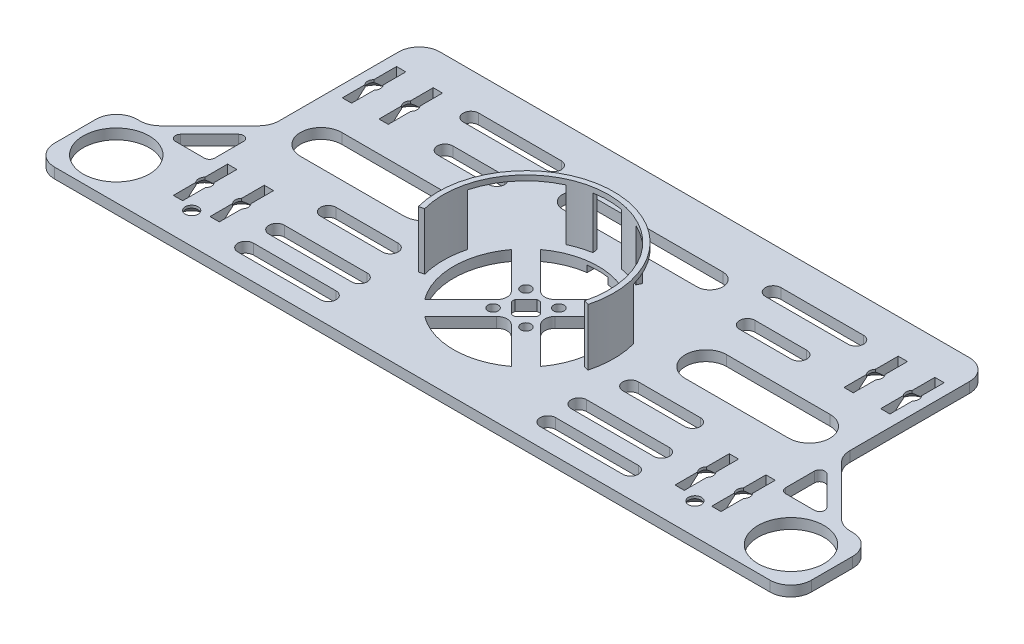
SolidWorks part; units mm, degrees
ref_plane "前视基准面" through (0, 0, 0) normal (0, 0, 1) x (1, 0, 0)
ref_plane "上视基准面" through (0, 0, 0) normal (0, 1, 0) x (1, 0, 0)
ref_plane "右视基准面" through (0, 0, 0) normal (1, 0, 0) x (0, 0, -1)
sketch "草图1" plane through (0, 0, 0) normal (0, 1, 0) x (1, 0, 0)
  line L0 (0, 0) -> (0, 46.1677) construction
  line L1 (-73.25, 0) -> (73.25, 0)
  line L2 (73.25, 0) -> (73.25, 16)
  line L8 (-73.25, 0) -> (-73.25, 16)
  line L9 (73.25, 16) -> (67.0784, 16)
  line L11 (55.25, 16) -> (55.25, 25)
  line L12 (55.25, 56.6) -> (-55.25, 56.6)
  line L13 (-55.25, 16) -> (-55.25, 25)
  line L14 (-73.25, 16) -> (-67.0784, 16)
  line L15 (64.25, 16) -> (55.25, 25)
  line L16 (67.0784, 16) -> (55.25, 27.8284)
  line L17 (55.25, 27.8284) -> (55.25, 56.6)
  line L18 (64.25, 16) -> (55.25, 16)
  line L19 (-67.0784, 16) -> (-55.25, 27.8284)
  line L20 (-64.25, 16) -> (-55.25, 25)
  line L21 (-64.25, 16) -> (-55.25, 16)
  line L22 (-55.25, 27.8284) -> (-55.25, 56.6)
  line L23 (0, 22) -> (7.4008, 22) construction
  line L24 (0, 22) -> (9.4181, 31.4181) construction
  line L25 (-11.2122, 30.3837) -> (8.3837, 10.7878)
  line L26 (11.2122, 13.6163) -> (-8.3837, 33.2122)
  line L27 (-11.2122, 13.6163) -> (8.3837, 33.2122)
  line L28 (11.2122, 30.3837) -> (-8.3837, 10.7878)
  line L29 (51.2, 17.25) -> (53, 6.75) construction
  line L30 (51.2, 17.25) -> (53, 17.25)
  line L31 (51.2, 17.25) -> (51.2, 6.75)
  line L32 (51.2, 6.75) -> (53, 6.75)
  line L33 (53, 17.25) -> (53, 6.75)
  line L34 (-51.2, 6.75) -> (-53, 6.75)
  line L35 (-53, 17.25) -> (-53, 6.75)
  line L36 (-51.2, 17.25) -> (-53, 17.25)
  line L37 (-51.2, 17.25) -> (-51.2, 6.75)
  line L38 (52.1, 0) -> (52.1, 56.6) construction
  line L39 (51.2, 49.95) -> (53, 39.45) construction
  line L40 (51.2, 49.95) -> (53, 49.95)
  line L41 (51.2, 49.95) -> (51.2, 39.45)
  line L42 (51.2, 39.45) -> (53, 39.45)
  line L43 (53, 49.95) -> (53, 39.45)
  line L44 (-51.2, 49.95) -> (-53, 39.45) construction
  line L45 (-51.2, 49.95) -> (-51.2, 39.45)
  line L46 (-51.2, 39.45) -> (-53, 39.45)
  line L47 (-53, 49.95) -> (-53, 39.45)
  line L48 (-51.2, 49.95) -> (-53, 49.95)
  line L49 (44.1, 17.25) -> (45.9, 17.25)
  line L50 (44.1, 17.25) -> (44.1, 6.75)
  line L51 (44.1, 6.75) -> (45.9, 6.75)
  line L52 (45.9, 17.25) -> (45.9, 6.75)
  line L53 (44.1, 49.95) -> (45.9, 49.95)
  line L54 (44.1, 49.95) -> (44.1, 39.45)
  line L55 (44.1, 39.45) -> (45.9, 39.45)
  line L56 (45.9, 49.95) -> (45.9, 39.45)
  line L57 (44.1, 49.95) -> (45.9, 39.45)
  line L58 (44.1, 17.25) -> (45.9, 6.75)
  line L59 (45, 56.6) -> (45, 0) construction
  line L60 (-44.1, 17.25) -> (-44.1, 6.75)
  line L61 (-44.1, 6.75) -> (-45.9, 6.75)
  line L62 (-45.9, 17.25) -> (-45.9, 6.75)
  line L63 (-44.1, 17.25) -> (-45.9, 17.25)
  line L64 (-44.1, 49.95) -> (-44.1, 39.45)
  line L65 (-44.1, 39.45) -> (-45.9, 39.45)
  line L66 (-45.9, 49.95) -> (-45.9, 39.45)
  line L67 (-44.1, 49.95) -> (-45.9, 49.95)
  line L68 (-52.1, 0) -> (-52.1, 56.6) construction
  line L69 (-45, 56.6) -> (-45, 0) construction
  line L70 (-13, 44.6) -> (13, 44.6) construction
  line L71 (-13, 47.1) -> (13, 47.1)
  line L72 (-13, 42.1) -> (13, 42.1)
  circle A2 centre (65.3, 8) radius 6.4
  circle A3 centre (-65.3, 8) radius 6.4
  circle A4 centre (0, 22) radius 4.5 construction
  circle A5 centre (3.182, 25.182) radius 1
  circle A6 centre (3.182, 18.818) radius 1
  circle A7 centre (-3.182, 18.818) radius 1
  circle A8 centre (-3.182, 25.182) radius 1
  circle A9 centre (0, 22) radius 14
  circle A11 centre (0, 22) radius 2.5
  arc A12 (-13, 47.1) -> (-13, 42.1) centre (-13, 44.6) ccw
  arc A13 (13, 42.1) -> (13, 47.1) centre (13, 44.6) ccw
  circle A14 centre (48.7, 6) radius 1
  circle A15 centre (-48.7, 6) radius 1
  point P3 (0, 56.6)
  point P18 (0, 0)
  point P19 (73.25, 8)
  point P26 (0, 22)
  point P55 (52.1, 12)
  point P66 (52.1, 44.7)
  point P67 (53, 44.7)
  point P68 (53, 12)
  point P85 (45, 44.7)
  point P100 (0, 44.6)
  dimension "D1" = 12.8
  dimension "D5" = 110.5
  dimension "D12" = 9
  dimension "D13" = 2
  dimension "D15" = 28
  dimension "D16" = 2
  dimension "D17" = 5
  dimension "D31" = 12
  dimension "D33" = 2
  dimension "D2" = 130.6
  dimension "D3" = 146.5
  dimension "D4" = 16
  dimension "D6" = 45
  dimension "D7" = 2
  dimension "D8" = 9
  dimension "D9" = 1.8
  dimension "D10" = 56.6
  dimension "D11" = 22
  dimension "D18" = 4
  dimension "D19" = 10.5
  dimension "D20" = 12
  dimension "D21" = 106
  dimension "D22" = 32.7
  dimension "D23" = 10.5
  dimension "D24" = 1.8
  dimension "D25" = 10.5
  dimension "D26" = 1.8
  dimension "D27" = 10.5
  dimension "D28" = 1.8
  dimension "D29" = 90
  dimension "D30" = 2.5
  dimension "D32" = 26
  dimension "D34" = 97.4
  dimension "D35" = 6
  dimension "D14" = 4
extrude "凸台-拉伸1" add sketch "草图1" along normal blind 2 contours L22 L19 L14 L8 L1 L2 L9 L16 L17 L12 A3 A2 L67 L64 L65 L66 L63 L60 L61 L62 L48 L45 L46 L47 L21 L20 L13 L15 L18 L11 L30 L33 L32 L31 L36 L37 L34 L35 L40 L43 L42 | A11 L25 L27 A9 L28 A7 | A11 L28 L25 A9 L26 A6 | A11 L26 L28 A9 L27 A5 | A11 L27 L26 A9 L25 A8 | L26 A11 | A11 L26 L27 | A11 L27 L25 | A11 L25 L28 | A11 L28 L26 | L28 A11 | L25 A11 | L27 A11
fillet "圆角1" radius 2 4 edges at (0, 1, -24.8284) (-2.8284, 1, -22) (0, 1, -19.1716) (2.8284, 1, -22)
fillet "圆角2" radius 4 10 edges at (67.0784, 1, -16) (55.25, 1, -27.8284) (-67.0784, 1, -16) (-55.25, 1, -27.8284) (-55.25, 1, -56.6) (55.25, 1, -56.6) (73.25, 1, -16) (73.25, 1, 0) (-73.25, 1, -16) (-73.25, 1, 0)
fillet "圆角3" radius 1 6 edges at (-55.25, 1, -16) (-64.25, 1, -16) (-55.25, 1, -25) (55.25, 1, -16) (55.25, 1, -25) (64.25, 1, -16)
sketch "草图10" plane through (0, 0, 0) normal (0, -1, 0) x (1, 0, 0)
  line L0 (0, 0) -> (0, -49.8475) construction
  line L1 (27.25, -29.6) -> (47.25, -29.6) construction
  line L2 (27.25, -25.6) -> (47.25, -25.6)
  line L3 (27.25, -33.6) -> (47.25, -33.6)
  line L4 (51.25, -56.6) -> (-51.25, -56.6) construction
  line L5 (55.25, -29.4853) -> (55.25, -52.6) construction
  line L6 (-27.25, -29.6) -> (-47.25, -29.6) construction
  line L7 (-27.25, -25.6) -> (-47.25, -25.6)
  line L8 (-27.25, -33.6) -> (-47.25, -33.6)
  line L9 (23.25, -19) -> (35.25, -19) construction
  line L10 (23.25, -17.5) -> (35.25, -17.5)
  line L11 (23.25, -20.5) -> (35.25, -20.5)
  line L12 (21.25, -11) -> (37.25, -11) construction
  line L13 (21.25, -9.5) -> (37.25, -9.5)
  line L14 (21.25, -12.5) -> (37.25, -12.5)
  line L15 (21.25, -5) -> (37.25, -5) construction
  line L16 (21.25, -3.5) -> (37.25, -3.5)
  line L17 (21.25, -6.5) -> (37.25, -6.5)
  line L18 (24.25, -40.6) -> (34.25, -40.6) construction
  line L19 (24.25, -39.1) -> (34.25, -39.1)
  line L20 (24.25, -42.1) -> (34.25, -42.1)
  line L21 (21.25, -48.6) -> (37.25, -48.6) construction
  line L22 (21.25, -47.1) -> (37.25, -47.1)
  line L23 (21.25, -50.1) -> (37.25, -50.1)
  line L24 (-69.25, 0) -> (69.25, 0) construction
  line L25 (-21.25, -5) -> (-37.25, -5) construction
  line L26 (-21.25, -3.5) -> (-37.25, -3.5)
  line L27 (-21.25, -6.5) -> (-37.25, -6.5)
  line L28 (-21.25, -11) -> (-37.25, -11) construction
  line L29 (-21.25, -9.5) -> (-37.25, -9.5)
  line L30 (-21.25, -12.5) -> (-37.25, -12.5)
  line L31 (-23.25, -19) -> (-35.25, -19) construction
  line L32 (-23.25, -17.5) -> (-35.25, -17.5)
  line L33 (-23.25, -20.5) -> (-35.25, -20.5)
  line L34 (-21.25, -48.6) -> (-37.25, -48.6) construction
  line L35 (-21.25, -47.1) -> (-37.25, -47.1)
  line L36 (-21.25, -50.1) -> (-37.25, -50.1)
  line L37 (-24.25, -40.6) -> (-34.25, -40.6) construction
  line L38 (-24.25, -39.1) -> (-34.25, -39.1)
  line L39 (-24.25, -42.1) -> (-34.25, -42.1)
  arc A0 (27.25, -25.6) -> (27.25, -33.6) centre (27.25, -29.6) ccw
  arc A1 (47.25, -33.6) -> (47.25, -25.6) centre (47.25, -29.6) ccw
  arc A2 (-27.25, -25.6) -> (-27.25, -33.6) centre (-27.25, -29.6) cw
  arc A3 (-47.25, -33.6) -> (-47.25, -25.6) centre (-47.25, -29.6) cw
  arc A4 (23.25, -17.5) -> (23.25, -20.5) centre (23.25, -19) ccw
  arc A5 (35.25, -20.5) -> (35.25, -17.5) centre (35.25, -19) ccw
  arc A6 (21.25, -9.5) -> (21.25, -12.5) centre (21.25, -11) ccw
  arc A7 (37.25, -12.5) -> (37.25, -9.5) centre (37.25, -11) ccw
  arc A8 (21.25, -3.5) -> (21.25, -6.5) centre (21.25, -5) ccw
  arc A9 (37.25, -6.5) -> (37.25, -3.5) centre (37.25, -5) ccw
  arc A10 (24.25, -39.1) -> (24.25, -42.1) centre (24.25, -40.6) ccw
  arc A11 (34.25, -42.1) -> (34.25, -39.1) centre (34.25, -40.6) ccw
  arc A12 (21.25, -47.1) -> (21.25, -50.1) centre (21.25, -48.6) ccw
  arc A13 (37.25, -50.1) -> (37.25, -47.1) centre (37.25, -48.6) ccw
  arc A14 (-21.25, -3.5) -> (-21.25, -6.5) centre (-21.25, -5) cw
  arc A15 (-37.25, -6.5) -> (-37.25, -3.5) centre (-37.25, -5) cw
  arc A16 (-21.25, -9.5) -> (-21.25, -12.5) centre (-21.25, -11) cw
  arc A17 (-37.25, -12.5) -> (-37.25, -9.5) centre (-37.25, -11) cw
  arc A18 (-23.25, -17.5) -> (-23.25, -20.5) centre (-23.25, -19) cw
  arc A19 (-35.25, -20.5) -> (-35.25, -17.5) centre (-35.25, -19) cw
  arc A20 (-21.25, -47.1) -> (-21.25, -50.1) centre (-21.25, -48.6) cw
  arc A21 (-37.25, -50.1) -> (-37.25, -47.1) centre (-37.25, -48.6) cw
  arc A22 (-24.25, -39.1) -> (-24.25, -42.1) centre (-24.25, -40.6) cw
  arc A23 (-34.25, -42.1) -> (-34.25, -39.1) centre (-34.25, -40.6) cw
  point P6 (37.25, -29.6)
  point P16 (29.25, -19)
  point P19 (-37.25, -29.6)
  point P30 (29.25, -11)
  point P37 (29.25, -5)
  point P44 (29.25, -40.6)
  point P51 (29.25, -48.6)
  point P62 (-29.25, -5)
  point P69 (-29.25, -11)
  point P76 (-29.25, -19)
  point P83 (-29.25, -48.6)
  point P90 (-29.25, -40.6)
  dimension "D1" = 4
  dimension "D2" = 23
  dimension "D3" = 8
  dimension "D4" = 20
  dimension "D5" = 16
  dimension "D6" = 16
  dimension "D7" = 12
  dimension "D8" = 10
  dimension "D9" = 16
  dimension "D10" = 3
  dimension "D11" = 3
  dimension "D12" = 3
  dimension "D13" = 3
  dimension "D14" = 3
  dimension "D15" = 6
  dimension "D16" = 8
  dimension "D17" = 5
  dimension "D18" = 26
  dimension "D19" = 8
  dimension "D20" = 8
extrude "切除-拉伸1" cut sketch "草图10" against normal up to surface (2 mm away) up to face at (0, 2, -22)
hole_wizard "M2.5 平头机械螺钉的锥形沉头孔1" positions "草图11" profile "草图12" countersink size "M2.5" standard "ANSI Metric" end condition up to next
sketch "草图11" plane through (0, 0, 0) normal (0, -1, 0) x (-1, 0, 0)
  point P0 (-52.1, 44.7)
  point P2 (-45, 44.7)
  point P4 (45, 44.7)
  point P6 (52.1, 44.7)
  point P8 (52.1, 12)
  point P10 (45, 12)
  point P12 (-45, 12)
  point P14 (-52.1, 12)
  point P16 (-48.7, 6)
  point P19 (48.7, 6)
sketch "草图12" plane through (52.1, 0, -44.7) normal (1, 0, 0) x (0, 0, -1)
  line L0 (0, 0) -> (0, 2)
  line L1 (0, 2) -> (1.25, 2)
  line L2 (1.25, 2) -> (1.25, 1.5)
  line L3 (1.25, 1.5) -> (2.75, 0)
  line L5 (2.75, 0) -> (0, 0)
  line L6 (-1.25, 1.5) -> (-2.75, 0) construction
  line L11 (0, -6.35) -> (0, 107.95) construction
  dimension "通孔孔直径" = 2.5
  dimension "通孔孔深度" = 2
  dimension "近端锥形沉头孔直径" = 5.5
  dimension "近端锥形沉头孔角度" = 90
sketch "草图13" plane through (0, 2, 0) normal (0, 1, 0) x (1, 0, 0)
  line L0 (0, 0) -> (0, 56.6) construction
  line L2 (0, 22) -> (20.9386, 22) construction
  line L3 (0, 22) -> (-16.4207, 17.6001)
  line L4 (0, 22) -> (-7.1845, 37.4072)
  line L5 (0, 22) -> (-2.952, 38.7417)
  line L6 (0, 22) -> (-16.4207, 26.3999)
  line L7 (0, 22) -> (2.952, 38.7417)
  line L8 (0, 22) -> (7.1845, 37.4072)
  line L9 (0, 22) -> (16.4207, 26.3999)
  line L10 (0, 22) -> (16.4207, 17.6001)
  circle A0 centre (0, 22) radius 16
  circle A1 centre (0, 22) radius 17
  dimension "D1" = 32
  dimension "D2" = 34
  dimension "D3" = 15
  dimension "D4" = 25
  dimension "D5" = 10
extrude "凸台-拉伸2" add sketch "草图13" along normal blind 10 contours L6 A1 L3 A0 | L5 A1 L4 A0 | L8 A1 L7 A0 | L10 A1 L9 A0
sketch "草图14" plane through (0, 12, 0) normal (0, 1, 0) x (1, 0, 0)
  line L0 (-15.4548, 17.8589) -> (-16.4207, 17.6001)
  line L1 (15.4548, 17.8589) -> (16.4207, 17.6001)
  circle A0 centre (0, 22) radius 16
  circle A1 centre (0, 22) radius 17
  line M3 (-15.4548, 26.1411) -> (-16.4207, 26.3999)
  arc M4 (-16.4207, 26.3999) -> (-16.4207, 17.6001) centre (0, 22) ccw
  line M5 (-16.4207, 17.6001) -> (-15.4548, 17.8589)
  arc M6 (-15.4548, 17.8589) -> (-15.4548, 26.1411) centre (0, 22) cw
extrude "凸台-拉伸3" add sketch "草图14" along normal blind 1 contours M6 M3 M4 M5 | L1 A1 A0 M3
sketch "草图15" plane through (0, 0, 0) normal (0, -1, 0) x (1, 0, 0)
  line L0 (-2, -42.1) -> (-2, -35.8564)
  line L1 (-13, -42.1) -> (13, -42.1) construction
  line L2 (0, -56.6) -> (0, 0) construction
  line L3 (51.25, -56.6) -> (-51.25, -56.6) construction
  line L4 (2, -42.1) -> (2, -35.8564)
  line L5 (-13, -42.1) -> (13, -42.1)
  arc A0 (-8.3837, -33.2122) -> (8.3837, -33.2122) centre (0, -22) ccw construction
  arc A1 (-8.3837, -33.2122) -> (8.3837, -33.2122) centre (0, -22) ccw
  dimension "D1" = 4
extrude "切除-拉伸2" cut sketch "草图15" against normal blind 1.25 contours L5 L2 A1 L0 | L2 L5 L4 A1
